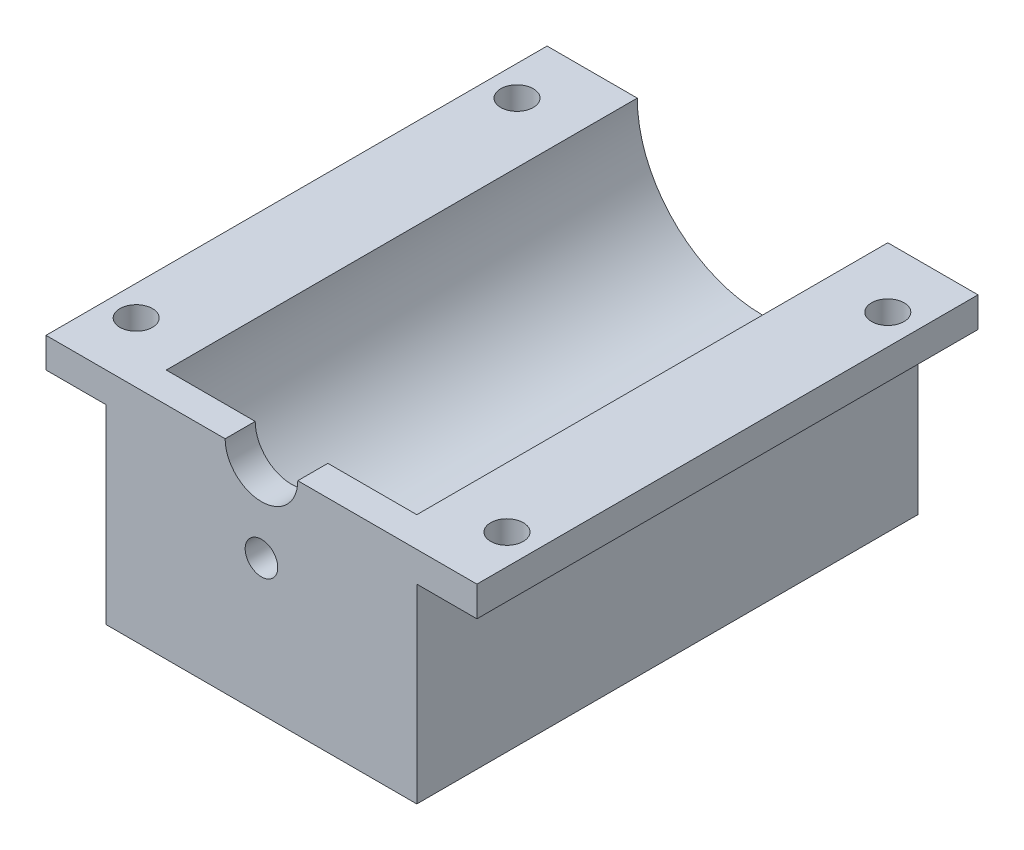
SolidWorks part; units mm, degrees
ref_plane "Plan de face" through (0, 0, 0) normal (0, 0, 1) x (1, 0, 0)
ref_plane "Plan de dessus" through (0, 0, 0) normal (0, 1, 0) x (1, 0, 0)
ref_plane "Plan de droite" through (0, 0, 0) normal (1, 0, 0) x (0, 0, -1)
sketch "Esquisse1" plane through (0, 0, 0) normal (0, 0, 1) x (1, 0, 0)
  line L5 (-6, 19) -> (-6, 22)
  line L6 (-6, 22) -> (3, 22)
  line L7 (37, 19) -> (37, 22)
  line L8 (37, 22) -> (28, 22)
  line L10 (-6, 19) -> (0, 19)
  line L17 (31, 19) -> (37, 19)
  line L18 (15.5, 0) -> (15.5, 22) construction
  line L19 (0, 19) -> (0, 0)
  line L20 (0, 0) -> (31, 0)
  line L21 (31, 0) -> (31, 19)
  arc A0 (3, 22) -> (28, 22) centre (15.5, 22) ccw
  dimension "D1" = 6
  dimension "D3" = 25
  dimension "D5" = 3
  dimension "D6" = 3
  dimension "D7" = 9
  dimension "D8" = 9
  dimension "D11" = 6
  dimension "D14" = 22
extrude "Boss.-Extru.1" add sketch "Esquisse1" along normal blind 50
sketch "Esquisse4" plane through (0, 22, 0) normal (0, 1, 0) x (1, 0, 0)
  line L0 (-1.5, 0) -> (-1.5, -50) construction
  line L1 (3, 0) -> (-6, 0) construction
  line L2 (3, -50) -> (-6, -50) construction
  line L3 (-6, -50) -> (-6, 0) construction
  line L4 (37, -50) -> (37, 0) construction
  line L5 (37, 0) -> (28, 0) construction
  line L6 (37, -50) -> (28, -50) construction
  circle A0 centre (-3, -44) radius 1.625
  circle A1 centre (34, -44) radius 1.625
  circle A2 centre (34, -6) radius 1.625
  circle A3 centre (-3, -6) radius 1.625
  dimension "D1" = 3.25
  dimension "D4" = 6
  dimension "D6" = 3
  dimension "D7" = 6
  dimension "D2" = 6
  dimension "D3" = 3
  dimension "D5" = 3
  dimension "D8" = 3
  dimension "D9" = 6
extrude "Enlèv. mat.-Extru.1" cut sketch "Esquisse4" against normal blind 50
sketch "Esquisse7" plane through (0, 0, 50) normal (0, 0, 1) x (1, 0, 0)
  line L0 (19.125, 22) -> (28, 22)
  line L1 (3, 22) -> (11.875, 22)
  line L2 (3, 22) -> (3, 9.5)
  line L3 (3, 9.5) -> (28, 9.5)
  line L4 (28, 22) -> (28, 9.5)
  arc A0 (11.875, 22) -> (19.125, 22) centre (15.5, 22) ccw
  circle A1 centre (15.5, 13.5) radius 1.625
  dimension "D1" = 8.5
  dimension "D2" = 3.25
  dimension "D3" = 7.25
  dimension "D4" = 25
extrude "Boss.-Extru.2" add sketch "Esquisse7" against normal blind 3
